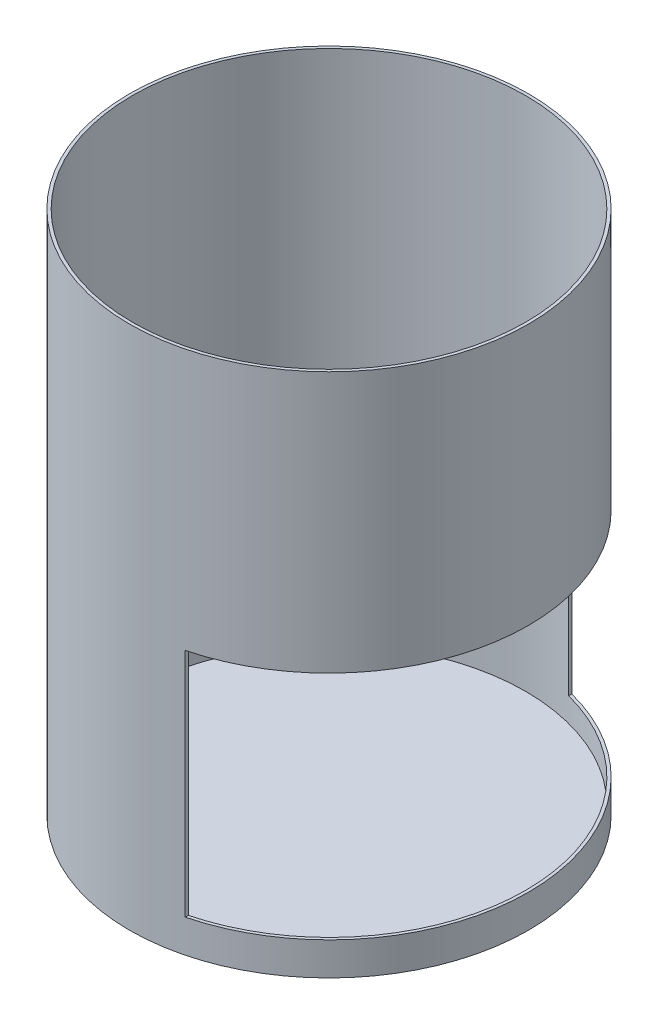
SolidWorks part; units mm, degrees
ref_plane "정면" through (0, 0, 0) normal (0, 0, 1) x (1, 0, 0)
ref_plane "윗면" through (0, 0, 0) normal (0, 1, 0) x (1, 0, 0)
ref_plane "우측면" through (0, 0, 0) normal (1, 0, 0) x (0, 0, -1)
sketch "스케치2" plane through (0, 0, 0) normal (0, 1, 0) x (1, 0, 0)
  circle A0 centre (0, 0) radius 66.5
  circle A1 centre (0, 0) radius 65.5
  dimension "D1" = 133
  dimension "D2" = 131
extrude "보스-돌출1" add sketch "스케치2" along normal blind 175
sketch "스케치3" plane through (0, 0, 0) normal (0, 1, 0) x (1, 0, 0)
  circle A0 centre (0, 0) radius 65.5
  dimension "D1" = 131
extrude "보스-돌출2" add sketch "스케치3" along normal blind 3
sketch "스케치4" plane through (0, 0, 0) normal (0, 0, 1) x (1, 0, 0)
  line L1 (66.5, 88) -> (16.5, 88)
  line L2 (66.5, 88) -> (66.5, 11)
  line L3 (66.5, 11) -> (16.5, 11)
  line L4 (16.5, 88) -> (16.5, 11)
  dimension "D1" = 50
  dimension "D3" = 77
extrude "컷-돌출1" cut sketch "스케치4" along normal through all and the other way through all
